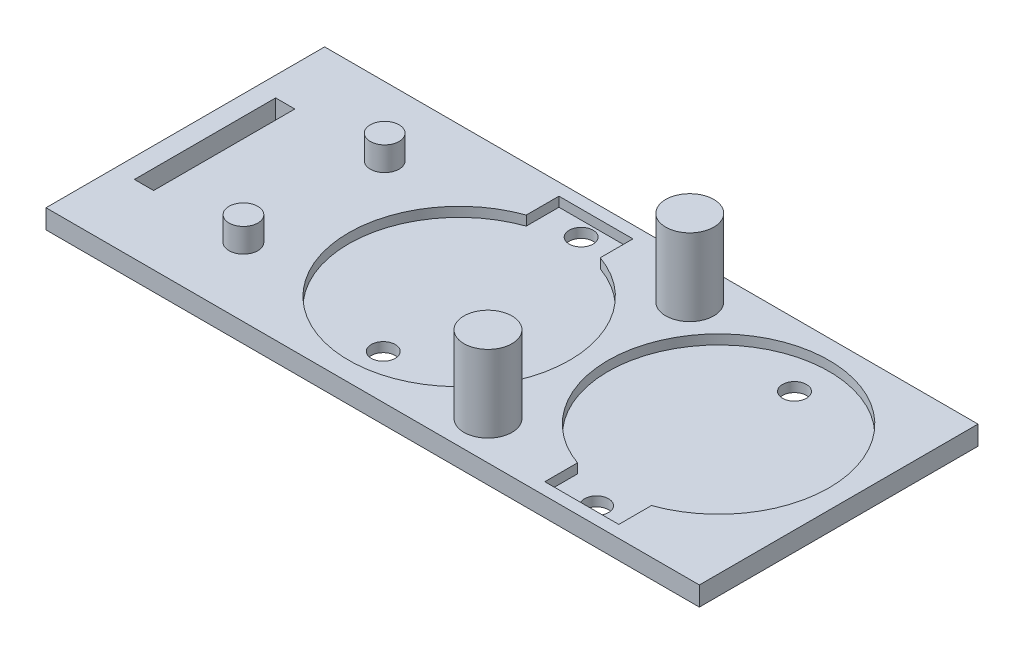
SolidWorks part; units mm, degrees
ref_plane "Front Plane" through (0, 0, 0) normal (0, 0, 1) x (1, 0, 0)
ref_plane "Top Plane" through (0, 0, 0) normal (0, 1, 0) x (1, 0, 0)
ref_plane "Right Plane" through (0, 0, 0) normal (1, 0, 0) x (0, 0, -1)
sketch "Sketch1" plane through (0, 0, 0) normal (0, 1, 0) x (1, 0, 0)
  line L1 (-27.5556, 17.0556) -> (40.4444, 17.0556)
  line L2 (-27.5556, 17.0556) -> (-27.5556, -11.9444)
  line L3 (-27.5556, -11.9444) -> (40.4444, -11.9444)
  line L4 (40.4444, 17.0556) -> (40.4444, -11.9444)
  dimension "D1" = 68
  dimension "D2" = 29
extrude "base" add sketch "Sketch1" along normal blind 2
sketch "Sketch2" plane through (0, 2, 0) normal (0, 1, 0) x (1, 0, 0)
  line L0 (-27.5556, -11.9444) -> (40.4444, -11.9444) construction
  line L1 (-27.5556, 17.0556) -> (-27.5556, -11.9444) construction
  circle A0 centre (-14.1556, -4.7944) radius 1.5
  dimension "D1" = 3
  dimension "D2" = 7.15
  dimension "D3" = 13.4
extrude "left peg" add sketch "Sketch2" along normal blind 2.5
sketch "Sketch3" plane through (0, 2, 0) normal (0, 1, 0) x (1, 0, 0)
  line L1 (-27.5556, 17.0556) -> (-27.5556, -11.9444) construction
  circle A0 centre (-14.1556, 9.9056) radius 1.5
  circle A1 centre (-14.1556, -4.7944) radius 1.5 construction
  dimension "D1" = 3
  dimension "D2" = 13.4
  dimension "D3" = 14.7
extrude "right peg" add sketch "Sketch3" along normal blind 2.5
sketch "Sketch4" plane through (0, 2, 0) normal (0, 1, 0) x (1, 0, 0)
  line L0 (40.4444, 17.0556) -> (-27.5556, 17.0556) construction
  line L1 (-25.5056, 9.9056) -> (-23.5056, 9.9056)
  line L2 (-25.5056, 9.9056) -> (-25.5056, -4.7944)
  line L3 (-25.5056, -4.7944) -> (-23.5056, -4.7944)
  line L4 (-23.5056, 9.9056) -> (-23.5056, -4.7944)
  circle A0 centre (-14.1556, -4.7944) radius 1.5 construction
  dimension "D1" = 2
  dimension "D2" = 14.7
  dimension "D3" = 7.15
  dimension "D4" = 9.35
extrude "accel wire hole" cut sketch "Sketch4" against normal blind 2.5
sketch "Sketch10" plane through (0, 2, 0) normal (0, 1, 0) x (1, 0, 0)
  line L0 (40.4444, -11.9444) -> (40.4444, 17.0556) construction
  line L1 (40.4444, 17.0556) -> (-27.5556, 17.0556) construction
  line L3 (23.0944, -7.2808) -> (30.7944, -7.2808)
  line L4 (23.0944, -7.2808) -> (23.0944, -10.6808)
  line L5 (23.0944, -10.6808) -> (30.7944, -10.6808)
  line L6 (30.7944, -7.2808) -> (30.7944, -10.6808)
  circle A0 centre (26.9444, 3.5556) radius 11.5
  dimension "D1" = 23
  dimension "D2" = 13.5
  dimension "D3" = 13.5
  dimension "D4" = 7.7
  dimension "D5" = 3.4
extrude "right battery" cut sketch "Sketch10" against normal blind 1 contours L3 A0 | L3 A0 | A0 L4 L5 L6
sketch "Sketch11" plane through (0, 2, 0) normal (0, 1, 0) x (1, 0, 0)
  line L0 (-27.5556, -11.9444) -> (40.4444, -11.9444) construction
  line L1 (40.4444, -11.9444) -> (40.4444, 17.0556) construction
  line L3 (-1.9056, 12.392) -> (5.7944, 12.392)
  line L4 (-1.9056, 12.392) -> (-1.9056, 15.792)
  line L5 (-1.9056, 15.792) -> (5.7944, 15.792)
  line L6 (5.7944, 12.392) -> (5.7944, 15.792)
  circle A0 centre (1.9444, 1.5556) radius 11.5
  dimension "D1" = 23
  dimension "D2" = 13.5
  dimension "D3" = 38.5
  dimension "D4" = 7.7
  dimension "D5" = 3.4
extrude "left battery" cut sketch "Sketch11" against normal blind 1 contours L3 A0 | A0 L6 L5 L4 | L3 A0
sketch "Sketch12" plane through (0, 1, 0) normal (0, 1, 0) x (1, 0, 0)
  line L0 (40.4444, -11.9444) -> (40.4444, 17.0556) construction
  circle A0 centre (1.9444, 14.2556) radius 1.25
  circle A1 centre (1.9444, -6.3444) radius 1.25
  arc A2 (-1.9056, 12.392) -> (5.7944, 12.392) centre (1.9444, 1.5556) ccw construction
  dimension "D1" = 2.5
  dimension "D2" = 2.5
  dimension "D3" = 38.5
  dimension "D4" = 38.5
  dimension "D5" = 20.6
  dimension "D6" = 7.9
extrude "Cut-Extrude10" cut sketch "Sketch12" against normal blind 1.5
sketch "Sketch13" plane through (0, 1, 0) normal (0, 1, 0) x (1, 0, 0)
  line L0 (40.4444, -11.9444) -> (40.4444, 17.0556) construction
  circle A0 centre (26.9444, 11.4556) radius 1.25
  circle A1 centre (26.9444, -9.1444) radius 1.25
  arc A2 (30.7944, -7.2808) -> (23.0944, -7.2808) centre (26.9444, 3.5556) ccw construction
  dimension "D1" = 2.5
  dimension "D2" = 2.5
  dimension "D3" = 13.5
  dimension "D4" = 13.5
  dimension "D5" = 20.6
  dimension "D6" = 7.9
extrude "Cut-Extrude11" cut sketch "Sketch13" against normal blind 1.5
sketch "Sketch14" plane through (0, 2, 0) normal (0, 1, 0) x (1, 0, 0)
  line L0 (40.4444, 17.0556) -> (-27.5556, 17.0556) construction
  line L1 (-27.5556, -11.9444) -> (40.4444, -11.9444) construction
  line L2 (40.4444, -11.9444) -> (40.4444, 17.0556) construction
  circle A0 centre (14.4444, 13.0556) radius 2.5
  circle A1 centre (14.4444, -7.9444) radius 2.5
  point P8 (0, 0)
  dimension "D1" = 5
  dimension "D2" = 5
  dimension "D3" = 4
  dimension "D4" = 4
  dimension "D5" = 26
extrude "Boss-Extrude1" add sketch "Sketch14" along normal blind 8
